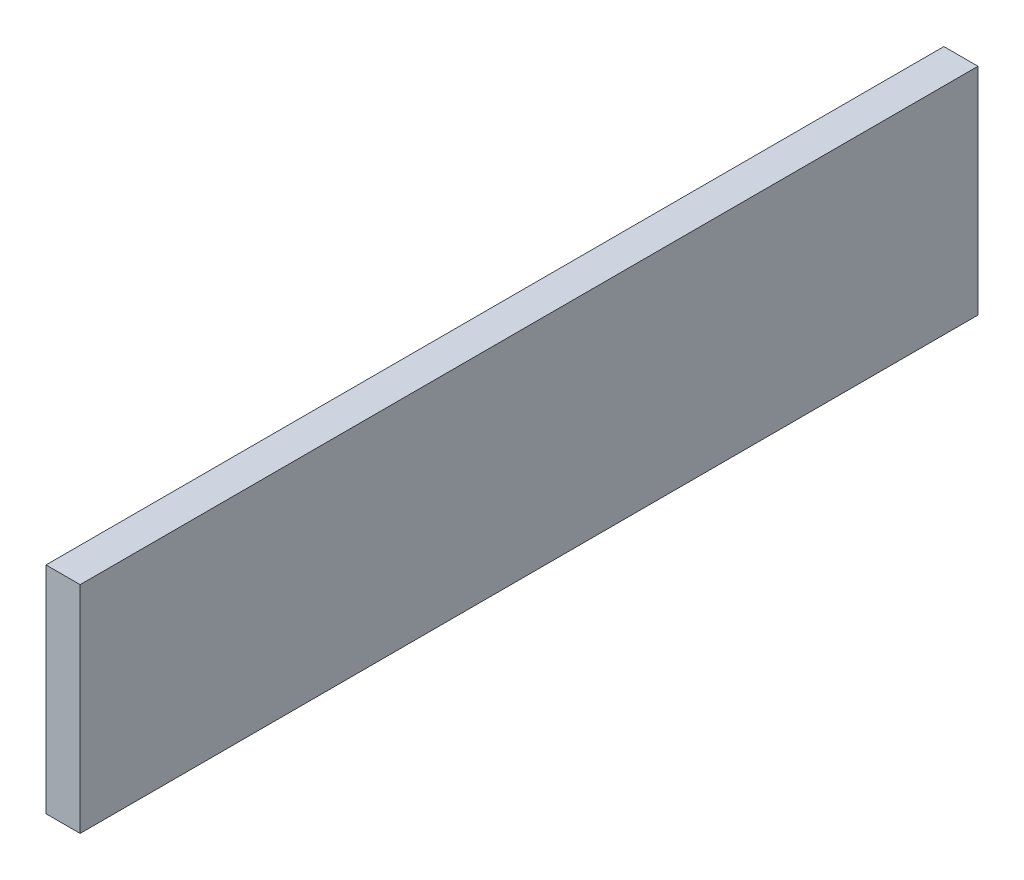
SolidWorks part; units mm, degrees
ref_plane "Front Plane" through (0, 0, 0) normal (0, 0, 1) x (1, 0, 0)
ref_plane "Top Plane" through (0, 0, 0) normal (0, 1, 0) x (1, 0, 0)
ref_plane "Right Plane" through (0, 0, 0) normal (1, 0, 0) x (0, 0, -1)
sketch "Sketch1" plane through (0, 0, 0) normal (1, 0, 0) x (0, 0, -1)
  line L1 (0, 0) -> (500, 0)
  line L2 (0, 0) -> (0, 120)
  line L3 (0, 120) -> (500, 120)
  line L4 (500, 0) -> (500, 120)
  dimension "D1" = 500
  dimension "D2" = 120
extrude "Boss-Extrude1" add sketch "Sketch1" along normal blind 19
